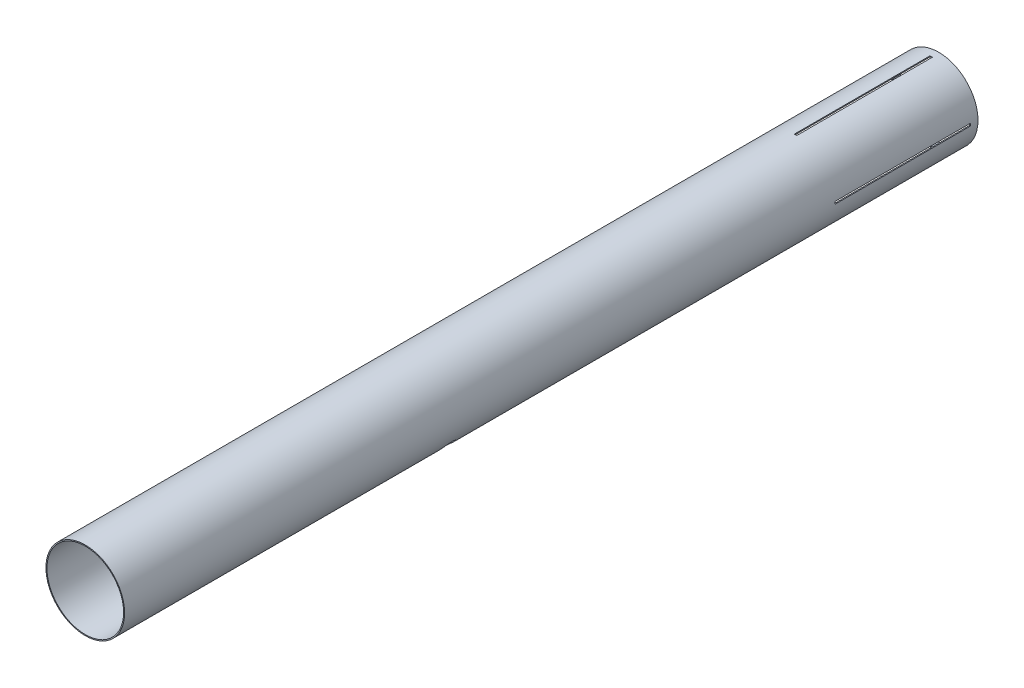
SolidWorks part; units mm, degrees
material "E-Glass Fiber"
ref_plane "Front" through (0, 0, 0) normal (0, 0, 1) x (1, 0, 0)
ref_plane "Top" through (0, 0, 0) normal (0, 1, 0) x (1, 0, 0)
ref_plane "Right" through (0, 0, 0) normal (1, 0, 0) x (0, 0, -1)
sketch "Sketch1" plane through (0, 0, 0) normal (0, 0, 1) x (1, 0, 0)
  circle A0 centre (0, 0) radius 78.35
  circle A1 centre (0, 0) radius 76.35
  dimension "D1" = 2
  dimension "D2" = 152.7
extrude "Boss-Extrude1" add sketch "Sketch1" along normal blind 1700
sketch "Sketch4" plane through (0, 0, 0) normal (0, 0, 1) x (1, 0, 0)
  line L0 (0, 0) -> (25.0476, -25.0476) construction
  line L1 (0, 0) -> (0, -24.8691) construction
  dimension "D1" = 45
ref_plane "Plane1" through (0, 0, 0) normal (0.7071, -0.7071, 0) x (0, 0, -1)
sketch "Sketch5" plane through (0, 0, 0) normal (0.7071, -0.7071, 0) x (0, 0, -1)
  line L0 (0, -78.35) -> (0, 78.35) construction
  circle A0 centre (-1034.89, 0) radius 15
  dimension "D1" = 30
  dimension "D2" = 1034.89
extrude "Cut-Extrude2" cut sketch "Sketch5" along normal through all
sketch "Sketch6" plane through (0, 0, 0) normal (0, 1, 0) x (1, 0, 0)
  line L0 (-2.4, -285) -> (-2.4, -15)
  line L1 (-2.4, -285) -> (2.4, -285)
  line L2 (-2.4, -15) -> (2.4, -15)
  line L3 (2.4, -285) -> (2.4, -15)
  line L4 (-2.4, -285) -> (2.4, -15) construction
  line L5 (-2.4, -15) -> (2.4, -285) construction
  line L6 (78.35, 0) -> (-78.35, 0) construction
  line L7 (0, 0) -> (0, -1700) construction
  line L8 (-78.35, -1700) -> (78.35, -1700) construction
  point P1 (0, -150)
  dimension "D1" = 15
  dimension "D2" = 4.8
  dimension "D3" = 270
extrude "Cut-Extrude3" cut sketch "Sketch6" against normal through all both and the other way through all
pattern_circular "CirPattern1" count 2 every 90 about axis through (0, 0, 0) along (0, 0, 1) of "Cut-Extrude3"
